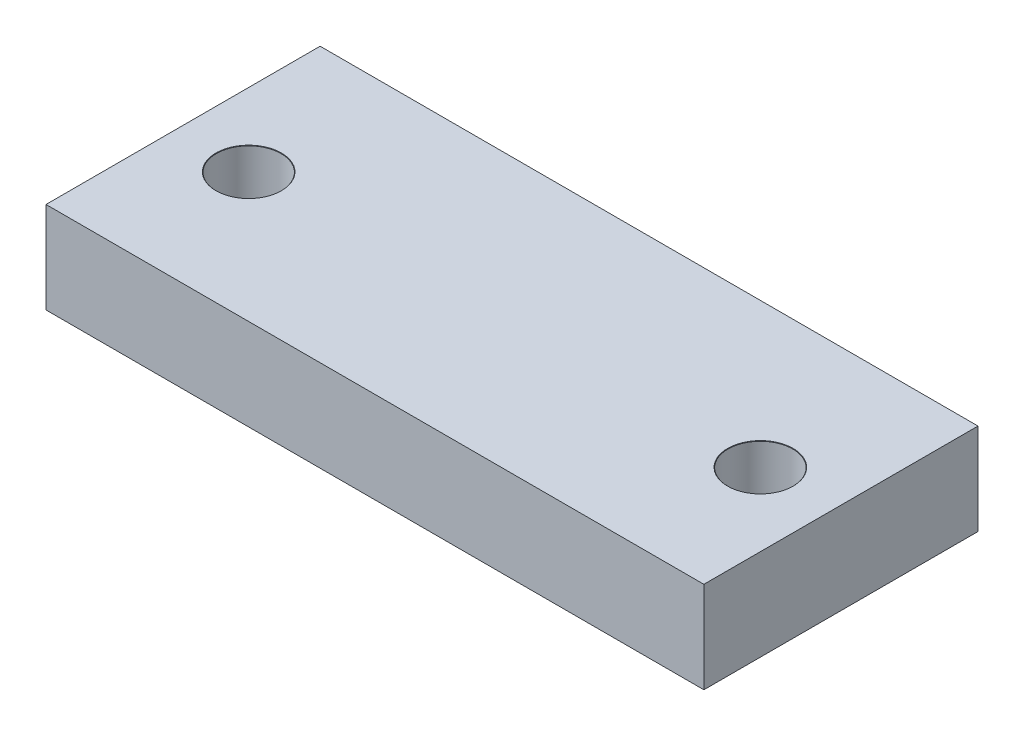
SolidWorks part; units mm, degrees
ref_plane "Front Plane" through (0, 0, 0) normal (0, 0, 1) x (1, 0, 0)
ref_plane "Top Plane" through (0, 0, 0) normal (0, 1, 0) x (1, 0, 0)
ref_plane "Right Plane" through (0, 0, 0) normal (1, 0, 0) x (0, 0, -1)
sketch "Sketch1" plane through (0, 0, 0) normal (0, 1, 0) x (1, 0, 0)
  line L0 (22.86, 19.05) -> (22.86, 0) construction
  line L1 (0, 0) -> (45.72, 0)
  line L2 (0, 0) -> (0, 19.05)
  line L3 (0, 19.05) -> (45.72, 19.05)
  line L4 (45.72, 0) -> (45.72, 19.05)
  point P5 (5.08, 9.0054)
  point P8 (5.08, 9.0054)
  point P9 (40.64, 9.0054)
  dimension "D1" = 17.78
  dimension "D2" = 45.72
  dimension "D3" = 19.05
extrude "Boss-Extrude1" add sketch "Sketch1" along normal mid plane 6.35
hole_wizard "M4 Clearance Hole1" positions "Sketch5" profile "Sketch4" hole size "M4" standard "ANSI Metric" end condition through all
sketch "Sketch5" plane through (0, 3.175, 0) normal (0, 1, 0) x (1, 0, 0)
  point P0 (5.08, 9.0054)
  point P3 (40.64, 9.0054)
sketch "Sketch4" plane through (5.08, 3.175, -9.0054) normal (1, 0, 0) x (0, 0, 1)
  line L0 (0, 0) -> (0, 6.35)
  line L1 (0, 6.35) -> (2.25, 6.35)
  line L2 (2.25, 6.35) -> (2.25, 0.025)
  line L3 (2.25, 0.025) -> (2.275, 0)
  line L5 (2.275, 0) -> (0, 0)
  line L6 (-2.25, 0.025) -> (-2.275, 0) construction
  line L11 (0, -6.35) -> (0, 107.95) construction
  dimension "Thru Hole Dia." = 4.5
  dimension "Thru Hole Depth" = 6.35
  dimension "Near C'Sink Dia." = 4.55
  dimension "Near C'Sink Angle" = 90
